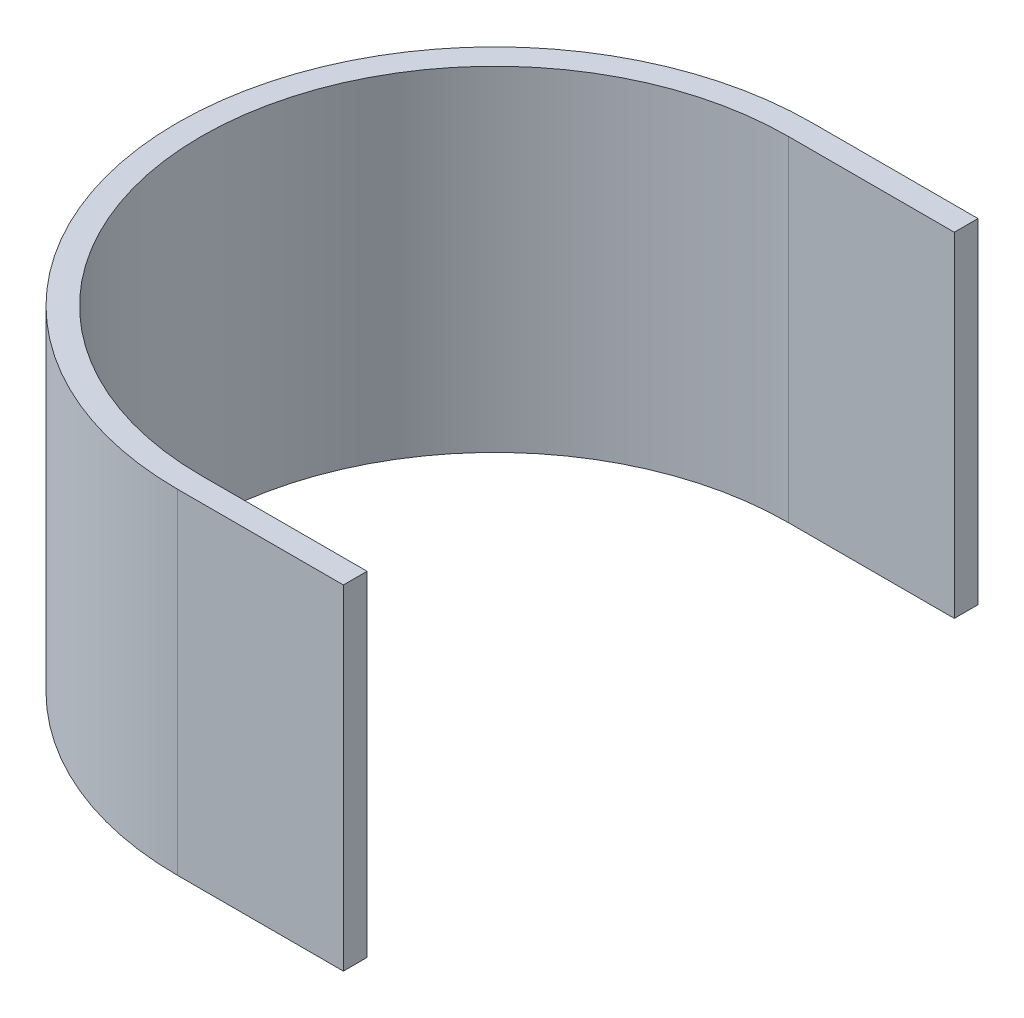
SolidWorks part; units mm, degrees
material "Carbon Fiber Orion"
ref_plane "Front Plane" through (0, 0, 0) normal (0, 0, 1) x (1, 0, 0)
ref_plane "Top Plane" through (0, 0, 0) normal (0, 1, 0) x (1, 0, 0)
ref_plane "Right Plane" through (0, 0, 0) normal (1, 0, 0) x (0, 0, -1)
sketch "Sketch1" plane through (0, 0, 0) normal (0, 1, 0) x (1, 0, 0)
  line L0 (24.7558, -3.3225) -> (37.357, -3.3225)
  line L1 (37.357, 41.2729) -> (24.7558, 41.2729)
  line L2 (37.357, 43.0729) -> (24.7558, 43.0729)
  line L3 (24.7558, -5.1225) -> (37.357, -5.1225)
  line L4 (37.357, 43.0729) -> (37.357, 41.2729)
  line L5 (37.357, -3.3225) -> (37.357, -5.1225)
  arc A0 (24.7558, 41.2729) -> (24.7558, -3.3225) centre (24.7558, 18.9752) ccw
  arc A1 (24.7558, 43.0729) -> (24.7558, -5.1225) centre (24.7558, 18.9752) ccw
  dimension "D1" = 1.8
extrude "Boss-Extrude1" add sketch "Sketch1" along normal blind 25.4
